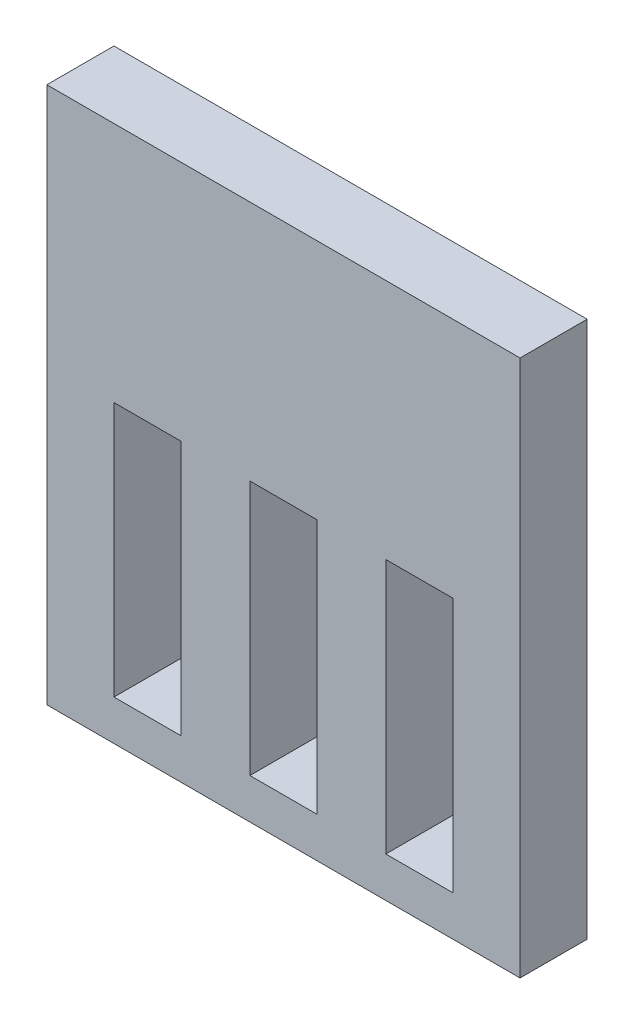
SolidWorks part; units mm, degrees
ref_plane "Front Plane" through (0, 0, 0) normal (0, 0, 1) x (1, 0, 0)
ref_plane "Top Plane" through (0, 0, 0) normal (0, 1, 0) x (1, 0, 0)
ref_plane "Right Plane" through (0, 0, 0) normal (1, 0, 0) x (0, 0, -1)
sketch "Sketch2" plane through (0, 0, 0) normal (0, 0, 1) x (1, 0, 0)
  line L0 (0, 0) -> (35.25, 0) construction
  line L1 (35.25, 0) -> (-35.25, 0) construction
  line L3 (-35.25, 0) -> (35.25, 0)
  line L4 (-35.25, 0) -> (-35.25, 80)
  line L5 (-35.25, 80) -> (35.25, 80)
  line L6 (35.25, 0) -> (35.25, 80)
  dimension "D1" = 35.25
  dimension "D2" = 70.5
  dimension "D3" = 80
  dimension "D4" = 70.5
extrude "Boss-Extrude1" add sketch "Sketch2" along normal blind 10
sketch "Sketch5" plane through (0, 0, 10) normal (0, 0, 1) x (1, 0, 0)
  line L0 (0, 80) -> (0, 74) construction
  line L1 (35.25, 80) -> (-35.25, 80) construction
  line L2 (0, 0) -> (0, 6) construction
  line L3 (-35.25, 0) -> (35.25, 0) construction
  line L4 (-35.25, 74) -> (-25.25, 74) construction
  line L5 (-35.25, 80) -> (-35.25, 0) construction
  line L6 (25.25, 6) -> (15.25, 6)
  line L7 (-25.25, 74) -> (-15.25, 74)
  line L8 (-25.25, 74) -> (-25.25, 6)
  line L9 (-25.25, 6) -> (-15.25, 6)
  line L10 (-15.25, 74) -> (-15.25, 6)
  line L15 (0, 6) -> (5, 6) construction
  line L16 (5, 6) -> (-5, 6)
  line L17 (5, 6) -> (5, 74)
  line L18 (5, 74) -> (-5, 74)
  line L19 (-5, 6) -> (-5, 74)
  line L20 (15.25, 74) -> (15.25, 6)
  line L21 (25.25, 74) -> (15.25, 74)
  line L22 (25.25, 74) -> (25.25, 6)
  dimension "D1" = 6
  dimension "D2" = 6
  dimension "D3" = 10
  dimension "D4" = 68
  dimension "D5" = 10
  dimension "D6" = 5
  dimension "D7" = 68
  dimension "D8" = 10
extrude "Cut-Extrude2" cut sketch "Sketch5" against normal blind 10
sketch "Sketch8" plane through (0, 0, 10) normal (0, 0, 1) x (1, 0, 0)
  line L0 (25.25, 6) -> (25.25, 74) construction
  line L1 (-25.25, 74) -> (25.25, 74)
  line L2 (-25.25, 74) -> (-25.25, 44)
  line L3 (-25.25, 44) -> (25.25, 44)
  line L4 (25.25, 74) -> (25.25, 44)
  dimension "D1" = 30
extrude "Boss-Extrude3" add sketch "Sketch8" against normal blind 10
